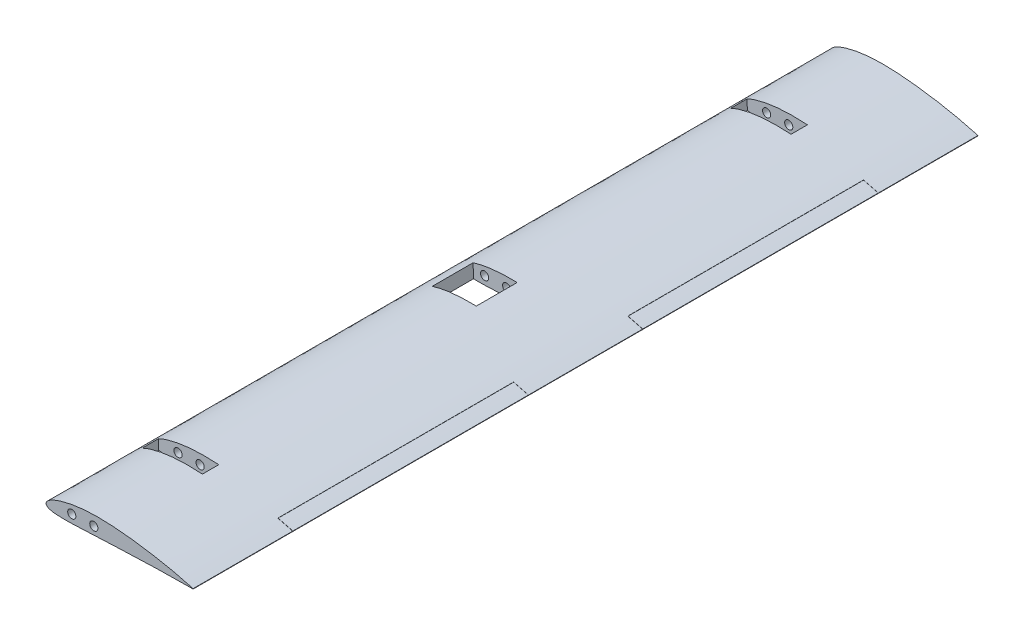
SolidWorks part; units mm, degrees
material "Polyurethane Foam Flexible"
ref_plane "Front Plane" through (0, 0, 0) normal (0, 0, 1) x (1, 0, 0)
ref_plane "Top Plane" through (0, 0, 0) normal (0, 1, 0) x (1, 0, 0)
ref_plane "Right Plane" through (0, 0, 0) normal (1, 0, 0) x (0, 0, -1)
curve "NACA 4412"
  spline degree 3 poles (25.4, 0.033, 0) (24.9771, 0.1481, 0) (24.1334, 0.3778, 0) (22.4431, 0.7955, 0) (20.3293, 1.2569, 0) (17.7869, 1.7118, 0) (15.2464, 2.0846, 0) (12.7045, 2.3505, 0) (10.1628, 2.5164, 0) (8.041, 2.5181, 0) (6.3469, 2.4009, 0) (5.0745, 2.2465, 0) (3.7995, 2.0188, 0) (2.7428, 1.745, 0) (1.8961, 1.4685, 0) (1.2577, 1.2074, 0) (0.7129, 0.9251, 0) (0.2401, 0.5874, 0) (-0.1715, 0.0442, 0) (0.2727, -0.3711, 0) (0.7261, -0.5342, 0) (1.266, -0.6443, 0) (1.9036, -0.7002, 0) (2.7513, -0.7398, 0) (3.8103, -0.7368, 0) (5.0806, -0.7013, 0) (6.3499, -0.6336, 0) (8.0433, -0.5544, 0) (10.1596, -0.4528, 0) (12.7001, -0.3574, 0) (15.2397, -0.2514, 0) (17.7796, -0.1611, 0) (20.3198, -0.0947, 0) (22.4366, -0.061, 0) (24.13, -0.0388, 0) (24.9767, -0.035, 0) (25.4, -0.033, 0) knots 0 0 0 0 0.025305 0.050488 0.10052 0.150191 0.199587 0.24874 0.297716 0.346601 0.371103 0.395726 0.42057 0.445825 0.458702 0.47192 0.485786 0.493461 0.506863 0.516148 0.522766 0.535269 0.547551 0.559786 0.584229 0.608681 0.633151 0.657622 0.706558 0.755482 0.804406 0.85332 0.902221 0.951113 0.975557 1 1 1 1
sketch "Sketch2" plane through (0, 0, 0) normal (0, 0, 1) x (1, 0, 0)
  line L1 (228.6, 12.387) -> (228.6, 11.7928)
  line L2 (40.005, 31.2493) -> (40.005, 5.6305) construction
  line L4 (74.2832, 19.3375) -> (40.005, 18.4399) construction
  line L5 (0, 0) -> (0, 12.7) construction
  line L6 (40.005, 18.4399) -> (60.8151, 18.4399) construction
  circle A0 centre (40.005, 18.4399) radius 6.35
  circle A1 centre (74.2832, 19.3375) radius 6.35
  spline S1 degree 3 poles (228.6, 12.387) (224.795, 13.4228) (217.2034, 15.4895) (201.9951, 19.2471) (182.9766, 23.3988) (160.101, 27.4914) (137.2432, 30.846) (114.3726, 33.2389) (91.504, 34.7313) (72.413, 34.7464) (57.1699, 33.6918) (45.7222, 32.3028) (34.2497, 30.2543) (24.7428, 27.7908) (17.1245, 25.3027) (11.3801, 22.9538) (6.4787, 20.4136) (2.2242, 17.375) (-1.4793, 12.488) (2.5182, 8.7506) (6.5972, 7.2835) (11.455, 6.2932) (17.1921, 5.7898) (24.819, 5.4335) (34.3469, 5.4602) (45.7763, 5.78) (57.1976, 6.389) (72.4334, 7.1015) (91.4748, 8.016) (114.3327, 8.8746) (137.1833, 9.8281) (160.036, 10.6401) (182.8906, 11.2375) (201.9369, 11.5408) (217.1729, 11.7405) (224.791, 11.7754) (228.6, 11.7928) knots 0 0 0 0 0.025305 0.050488 0.10052 0.150191 0.199587 0.24874 0.297716 0.346601 0.371103 0.395726 0.42057 0.445825 0.458702 0.47192 0.485786 0.493461 0.506863 0.516148 0.522766 0.535269 0.547551 0.559786 0.584229 0.608681 0.633151 0.657622 0.706558 0.755482 0.804406 0.85332 0.902221 0.951113 0.975557 1 1 1 1
  point P11 (40.005, 18.4399)
  dimension "D3" = 12.7
  dimension "D4" = 12.7
  dimension "D1" = 228.6
  dimension "D5" = 34.29
  dimension "D6" = 12.7
  dimension "D8" = 1.5
  dimension "D9" = 40.005
extrude "Extrude airfoil" add sketch "Sketch2" along normal blind 1219.2
sketch "Sketch3" plane through (0, 0, 0) normal (0, 1, 0) x (1, 0, 0)
  line L1 (228.6, -520.7) -> (205.74, -520.7)
  line L4 (205.74, -520.7) -> (205.74, -154.94)
  line L5 (228.6, -154.94) -> (205.74, -154.94)
  line L8 (0, 0) -> (0, -1219.2) construction
  line L9 (0, -609.6) -> (228.6, -609.6) construction
  line L10 (228.6, -1064.26) -> (228.6, -698.5)
  line L15 (228.6, -154.94) -> (228.6, -520.7)
  line L17 (228.6, -1219.2) -> (228.6, 0) construction
  line L18 (228.6, -1064.26) -> (205.74, -1064.26)
  line L19 (205.74, -698.5) -> (205.74, -1064.26)
  line L20 (228.6, -698.5) -> (205.74, -698.5)
  dimension "D1" = 22.86
  dimension "D2" = 365.76
  dimension "D3" = 88.9
extrude "Ailerons" cut sketch "Sketch3" against normal through all and the other way through all thin
ref_plane "Plane1" through (-0.4551, 17.3804, 0) normal (-0.0262, 0.9997, 0) x (0, 0, -1)
sketch "Sketch5" plane through (-0.4551, 17.3804, 0) normal (-0.0262, 0.9997, 0) x (0, 0, -1)
  line L0 (0, 0) -> (-1219.2, 0)
  line L1 (-609.6, 0) -> (-609.6, -227.3868) construction
  line L2 (-609.6, -57.15) -> (-1066.8, -57.15) construction
  line L3 (-139.7, -10.16) -> (-165.1, -104.14) construction
  line L4 (-1079.5, -104.14) -> (-1054.1, -104.14)
  line L5 (-1079.5, -104.14) -> (-1079.5, -10.16)
  line L6 (-1079.5, -10.16) -> (-1054.1, -10.16)
  line L7 (-1054.1, -104.14) -> (-1054.1, -10.16)
  line L8 (-1079.5, -104.14) -> (-1054.1, -10.16) construction
  line L9 (-1079.5, -10.16) -> (-1054.1, -104.14) construction
  line L10 (-139.7, -104.14) -> (-165.1, -10.16) construction
  line L11 (-165.1, -104.14) -> (-165.1, -10.16)
  line L12 (-139.7, -104.14) -> (-139.7, -10.16)
  line L13 (-139.7, -104.14) -> (-165.1, -104.14)
  line L14 (-139.7, -10.16) -> (-165.1, -10.16)
  line L16 (-577.85, -91.44) -> (-641.35, -91.44)
  line L17 (-577.85, -91.44) -> (-577.85, -22.86)
  line L18 (-577.85, -22.86) -> (-641.35, -22.86)
  line L19 (-641.35, -91.44) -> (-641.35, -22.86)
  point P19 (-609.6, -22.86)
  dimension "D1" = 1219.2
  dimension "D2" = 57.15
  dimension "D3" = 25.4
  dimension "D4" = 93.98
  dimension "D5" = 457.2
  dimension "D6" = 22.86
  dimension "D7" = 91.44
  dimension "D8" = 31.75
extrude "Cut-Extrude1" cut sketch "Sketch5" against normal through all and the other way through all contours L12 L14 L11 L13 | L7 L6 L5 L4 | L18 L19 L16 L17
equation "\"span\" = 48"
equation "\"D1@Extrude airfoil\"=\"span\""
equation "\"wing_chord\"= 9"
equation "\"D1@Sketch2\"= \"wing_chord\""
equation "\"D1@Sketch3\"=\"wing_chord\"*0.1"
equation "\"D2@Sketch3\"=\"span\"/2*0.6"
equation "\"fuse_len\"= 15"
equation "\"fuse_height\"= 5"
equation "\"fuse_wid\"= 5"
equation "\"foam_t\"= 0.1875"
equation "\"main_spar_len\"= 36"
equation "\"x_fuse_to_wing\"= 3"
equation "\"x_cg_from_le\"= 2.25"
equation "\"boom_len\"= 36"
equation "\"wing_spar_d\"= 0.5"
equation "\"wing_spar_spacing\"= 1.35"
equation "\"D3@Sketch2\"=\"wing_spar_d\""
equation "\"D4@Sketch2\"=\"wing_spar_d\""
equation "\"wing_angle\"= 1.5"
equation "\"boom_d\"= 0.75"
equation "\"wing_spar_l\"= 48"
equation "\"wing_mount_l\" = 2.5"
equation "\"D8@Sketch2\"=\"wing_angle\""
equation "\"D1@Sketch5\"=\"span\""
equation "\"D2@Sketch5\"=\"x_cg_from_le\""
equation "\"D3@Sketch5\"=\"boom_mount_l\""
equation "\"D5@Sketch5\"=\"boom_len\"/2"
equation "\"D5@Sketch2\"= \"wing_spar_spacing\""
equation "\"D9@Sketch2\"= \"x_cg_from_le\" - \"wing_spar_spacing\"/2"
equation "\"D6@Sketch5\"= \"x_cg_from_le\" - \"wing_spar_spacing\""
equation "\"D7@Sketch5\"= \"wing_chord\"*0.4"
equation "\"boom_mount_l\"= 1"
equation "\"vstab_span\"= 6.5"
equation "\"hstab_span\"= 15.25"
equation "\"tail_chord\"= 5"
equation "\"D8@Sketch5\"= \"wing_mount_l\"/2"
